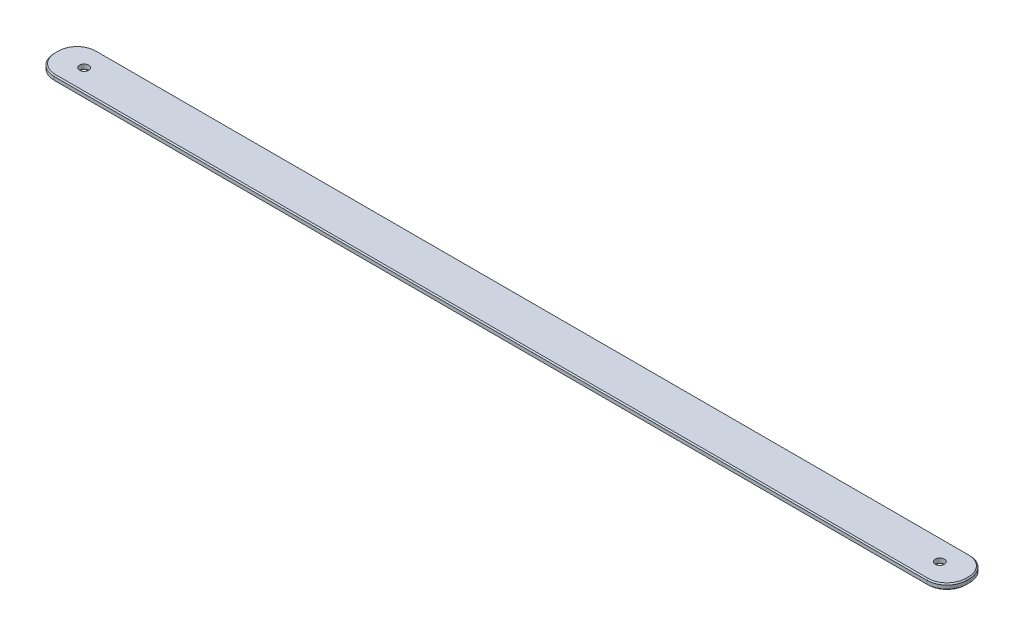
SolidWorks part; units mm, degrees
ref_plane "前视基准面" through (0, 0, 0) normal (0, 0, 1) x (1, 0, 0)
ref_plane "上视基准面" through (0, 0, 0) normal (0, 1, 0) x (1, 0, 0)
ref_plane "右视基准面" through (0, 0, 0) normal (1, 0, 0) x (0, 0, -1)
other "Configuration Table"
sketch "草图1" plane through (0, 0, 0) normal (0, 1, 0) x (1, 0, 0)
  line L1 (0, 0) -> (320, 0)
  line L2 (0, 0) -> (0, 15)
  line L3 (0, 15) -> (320, 15)
  line L4 (320, 0) -> (320, 15)
  dimension "D1" = 15
  dimension "D2" = 320
extrude "凸台-拉伸1" add sketch "草图1" along normal blind 2
sketch "草图2" plane through (0, 2, 0) normal (0, 1, 0) x (1, 0, 0)
  line L0 (0, 15) -> (0, 0) construction
  line L1 (320, 0) -> (320, 15) construction
  circle A0 centre (10, 7.5) radius 1.6
  circle A1 centre (310, 7.5) radius 1.6
  dimension "D1" = 3.2
  dimension "D2" = 10
  dimension "D3" = 3.2
  dimension "D4" = 10
extrude "切除-拉伸1" cut sketch "草图2" against normal blind 2
fillet "圆角1" radius 7 4 edges at (320, 1, -15) (320, 1, 0) (0, 1, 0) (0, 1, -15)
chamfer "倒角1" distance 0.4 angle 45 18 edges at (2.0503, 0, -12.9497) (0, 0, -7.5) (2.0503, 0, -2.0503) (160, 0, 0) (317.9497, 0, -2.0503) (320, 0, -7.5) (317.9497, 0, -12.9497) (160, 0, -15) (310, 0, -5.9) (10, 0, -5.9) (160, 2, -15) (2.0503, 2, -12.9497) (317.9497, 2, -12.9497) (0, 2, -7.5) (320, 2, -7.5) (2.0503, 2, -2.0503) (317.9497, 2, -2.0503) (160, 2, 0)
equation "\"D2@草图1\"=20*2 + 35*2 + 160+10*2 + 30"
